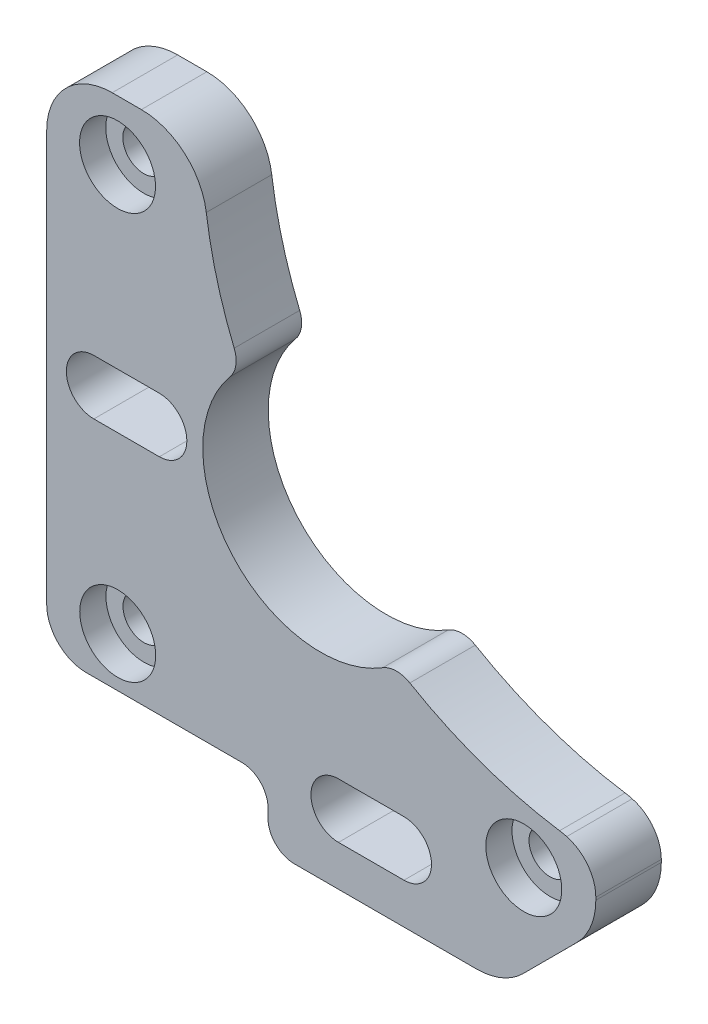
SolidWorks part; units mm, degrees
ref_plane "Front Plane" through (0, 0, 0) normal (0, 0, 1) x (1, 0, 0)
ref_plane "Top Plane" through (0, 0, 0) normal (0, 1, 0) x (1, 0, 0)
ref_plane "Right Plane" through (0, 0, 0) normal (1, 0, 0) x (0, 0, -1)
other "Configuration Table"
sketch "草图1" plane through (0, 0, 0) normal (0, 0, 1) x (1, 0, 0)
  line L1 (-25.3893, -42.5237) -> (-25.3893, -45.9237) construction
  line L2 (-46.5651, -25.5649) -> (-41.5651, -25.5649) construction
  line L3 (-48.6651, -25.5649) -> (-50.1651, -25.5649) construction
  line L4 (-46.5651, -23.4649) -> (-41.5651, -23.4649)
  line L5 (-39.486, -49.4263) -> (-13.6541, -49.4263)
  line L6 (-6.7642, -42.4718) -> (-6.7617, -42.0888)
  line L7 (-44.0651, -23.8649) -> (-44.0651, -27.2649) construction
  line L8 (-50.1651, -15.397) -> (-50.1651, -10.397)
  line L9 (-46.5651, -27.6649) -> (-41.5651, -27.6649)
  line L10 (-27.8893, -44.2237) -> (-22.8893, -44.2237) construction
  line L11 (-27.8893, -42.1237) -> (-22.8893, -42.1237)
  line L12 (-27.8893, -46.3237) -> (-22.8893, -46.3237)
  line L13 (-50.1651, -25.5649) -> (-50.1651, -15.397)
  line L14 (-45.1651, -5.397) -> (-42.9364, -5.397)
  line L15 (-50.1651, -25.5649) -> (-50.1651, -38.7472)
  line L16 (-13.6541, -49.4263) -> (-11.7642, -49.4263)
  line L17 (-6.7642, -44.4263) -> (-6.7642, -42.4718)
  line L18 (-50.1651, -38.7472) -> (-50.1651, -41.4263)
  line L19 (-45.1651, -46.4263) -> (-41.5651, -46.4263)
  line L20 (-41.5651, -46.4263) -> (-41.5651, -49.4263)
  line L21 (-41.5651, -49.4263) -> (-39.486, -49.4263)
  line L22 (-50.1651, -41.4263) -> (-50.1651, -46.4263)
  line L23 (-50.1651, -46.4263) -> (-45.1651, -46.4263)
  arc A5 (-46.5651, -23.4649) -> (-46.5651, -27.6649) centre (-46.5651, -25.5649) ccw
  arc A6 (-41.5651, -27.6649) -> (-41.5651, -23.4649) centre (-41.5651, -25.5649) ccw
  arc A7 (-27.8893, -42.1237) -> (-27.8893, -46.3237) centre (-27.8893, -44.2237) ccw
  arc A8 (-22.8893, -46.3237) -> (-22.8893, -42.1237) centre (-22.8893, -44.2237) ccw
  arc A12 (-37.9821, -9.7228) -> (-11.011, -37.1129) centre (-6.1957, -5.397) ccw
  circle A16 centre (-44.756, -9.941) radius 1.6
  circle A17 centre (-13.7419, -40.9269) radius 1.6
  circle A18 centre (-44.7419, -40.941) radius 1.6
  arc A19 (-6.7617, -42.0888) -> (-11.011, -37.1129) centre (-11.7616, -42.0563) ccw
  arc A20 (-37.9821, -9.7228) -> (-42.9364, -5.397) centre (-42.9364, -10.397) ccw
  arc A21 (-45.1651, -5.397) -> (-50.1651, -10.397) centre (-45.1651, -10.397) ccw
  arc A22 (-6.7642, -44.4263) -> (-11.7642, -49.4263) centre (-11.7642, -44.4263) cw
  circle A36 centre (-29.249, -25.434) radius 9
  point P22 (-44.0651, -25.5649)
  point P29 (-25.3893, -44.2237)
  dimension "D1" = 5
  dimension "D2" = 5
extrude "凸台-拉伸1" add sketch "草图1" along normal blind 5
sketch "草图2" plane through (0, 0, 5) normal (0, 0, -1) x (-1, 0, 0)
  circle A3 centre (44.756, -9.941) radius 2.9
  circle A4 centre (44.7419, -40.941) radius 2.9
  circle A5 centre (13.7419, -40.9269) radius 2.9
extrude "切除-拉伸1" cut sketch "草图2" along normal blind 2
sketch "草图3" plane through (0, 0, 0) normal (0, 0, -1) x (-1, 0, 0)
  line L0 (8.2413, -42.395) -> (12.2689, -46.4262)
  line L3 (50.2413, -44.7263) -> (50.2413, -51.3567)
  line L4 (50.2413, -51.3567) -> (5.0029, -51.3567)
  line L5 (5.0029, -51.3567) -> (5.0029, -38.1352)
  line L6 (5.0029, -38.1352) -> (8.2432, -38.1352)
  line L7 (8.2567, -8.4539) -> (8.2413, -42.395) construction
  line L8 (8.2432, -38.1352) -> (8.2413, -42.395)
  line L10 (41.5651, -49.4263) -> (11.7642, -49.4263) construction
  line L11 (33.2689, -49.4263) -> (15.2689, -49.4263)
  line L14 (33.2689, -49.4263) -> (33.2689, -44.7263)
  line L15 (33.2689, -44.7263) -> (48.6105, -44.7263)
  line L17 (12.2689, -46.4262) -> (15.2689, -49.4263)
  line L19 (48.6105, -44.7263) -> (50.2413, -44.7263)
extrude "切除-拉伸3" cut sketch "草图3" against normal through all
fillet "圆角1" radius 5 2 edges at (-8.2413, -42.395, 2.5) (-15.2689, -49.4263, 2.5)
fillet "圆角2" radius 3 1 edges at (-8.243, -38.5038, 2.5)
fillet "圆角4" radius 2 1 edges at (-33.2689, -49.4263, 2.5)
fillet "圆角6" radius 2 1 edges at (-33.2689, -44.7263, 2.5)
fillet "圆角7" radius 2 2 edges at (-35.338, -18.8064, 2.5) (-23.5344, -32.3869, 2.5)
fillet "圆角8" radius 3 1 edges at (-50.1651, -44.7263, 2.5)
